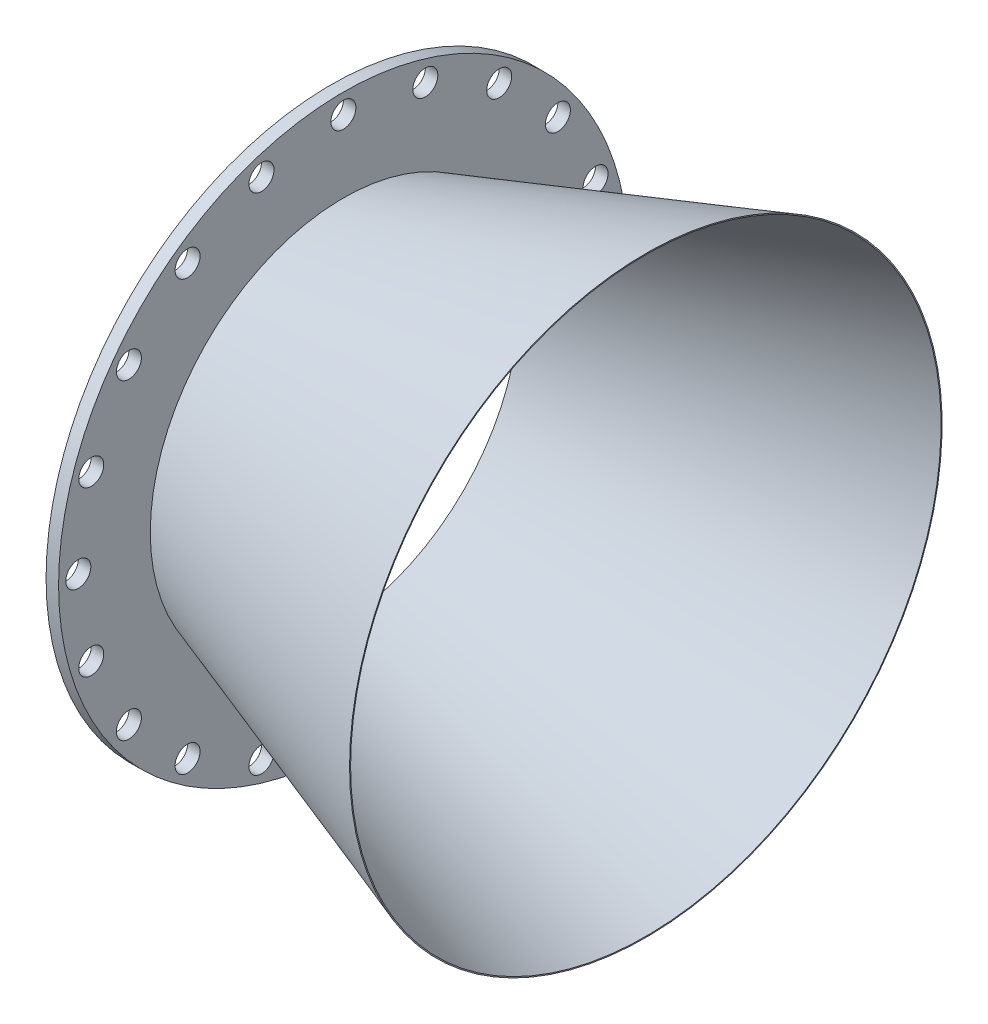
SolidWorks part; units mm, degrees
material "Tungsten"
ref_plane "Front Plane" through (0, 0, 0) normal (0, 0, 1) x (1, 0, 0)
ref_plane "Top Plane" through (0, 0, 0) normal (0, 1, 0) x (1, 0, 0)
ref_plane "Right Plane" through (0, 0, 0) normal (1, 0, 0) x (0, 0, -1)
sketch "Sketch1" plane through (0, 0, 0) normal (0, 0, 1) x (1, 0, 0)
  line L0 (0, 0) -> (0, 47.6758) construction
  line L1 (0, 0) -> (79.9592, 0) construction
  line L2 (79.9592, 0) -> (79.9592, 74.9554) construction
  line L3 (0, 47.6758) -> (45.8899, 47.6758) construction
  line L4 (0, 47.6758) -> (62.4191, 65.9935) construction
  line L5 (79.9592, 74.9554) -> (173.3924, 74.9554) construction
  line L6 (79.9592, 74.9554) -> (185.7919, 93.6166) construction
  line L10 (0, 47.6758) -> (79.9592, 74.9554)
  line L11 (0, 47.9442) -> (79.9592, 75.2238)
  line L12 (79.9592, 74.9554) -> (79.9592, 75.2238)
  line L13 (0, 47.6758) -> (0, 47.9442)
  line L14 (-0.082, 47.9162) -> (79.8772, 75.1958) construction
  dimension "D1" = 79.9592
  dimension "D2" = 47.6758
  dimension "D3" = 74.9554
  dimension "D4" = 16.355
  dimension "D5" = 10
  dimension "D6" = 0.254
revolve "Revolve1" add sketch "Sketch1" angle 360 about L1
sketch "Sketch3" plane through (0, 0, 0) normal (0, 0, 1) x (1, 0, 0)
  line L0 (79.9592, 75.2238) -> (0, 47.9442) construction
  line L1 (0, 47.9442) -> (3.175, 49.0274)
  line L2 (3.175, 49.0274) -> (3.175, 72.3138)
  line L3 (3.175, 72.3138) -> (0, 72.3138)
  line L4 (0, 72.3138) -> (0, 47.9442)
  line L5 (0, 0) -> (50000, 0) construction
  line L6 (0, 47.9442) -> (0, -47.9442) construction
  point P12 (0, 0)
  dimension "D1" = 3.175
  dimension "D2" = 72.3138
revolve "Revolve2" add sketch "Sketch3" angle 360 about L5
sketch "Sketch4" plane through (0, 0, 0) normal (-1, 0, 0) x (0, 0, 1)
  circle A0 centre (0, 67.31) radius 3.175
  circle A1 centre (20.7999, 64.0156) radius 3.175
  circle A2 centre (39.5638, 54.4549) radius 3.175
  circle A3 centre (54.4549, 39.5638) radius 3.175
  circle A4 centre (64.0156, 20.7999) radius 3.175
  circle A5 centre (67.31, 0) radius 3.175
  circle A6 centre (64.0156, -20.7999) radius 3.175
  circle A7 centre (54.4549, -39.5638) radius 3.175
  circle A8 centre (39.5638, -54.4549) radius 3.175
  circle A9 centre (20.7999, -64.0156) radius 3.175
  circle A10 centre (0, -67.31) radius 3.175
  circle A11 centre (-20.7999, -64.0156) radius 3.175
  circle A12 centre (-39.5638, -54.4549) radius 3.175
  circle A13 centre (-54.4549, -39.5638) radius 3.175
  circle A14 centre (-64.0156, -20.7999) radius 3.175
  circle A15 centre (-67.31, 0) radius 3.175
  circle A16 centre (-64.0156, 20.7999) radius 3.175
  circle A17 centre (-54.4549, 39.5638) radius 3.175
  circle A18 centre (-39.5638, 54.4549) radius 3.175
  circle A19 centre (-20.7999, 64.0156) radius 3.175
  point P44 (0, 0)
  dimension "D2" = 6.35
  dimension "D1" = 67.31
  dimension "D3" = 20
extrude "Cut-Extrude1" cut sketch "Sketch4" against normal up to next
